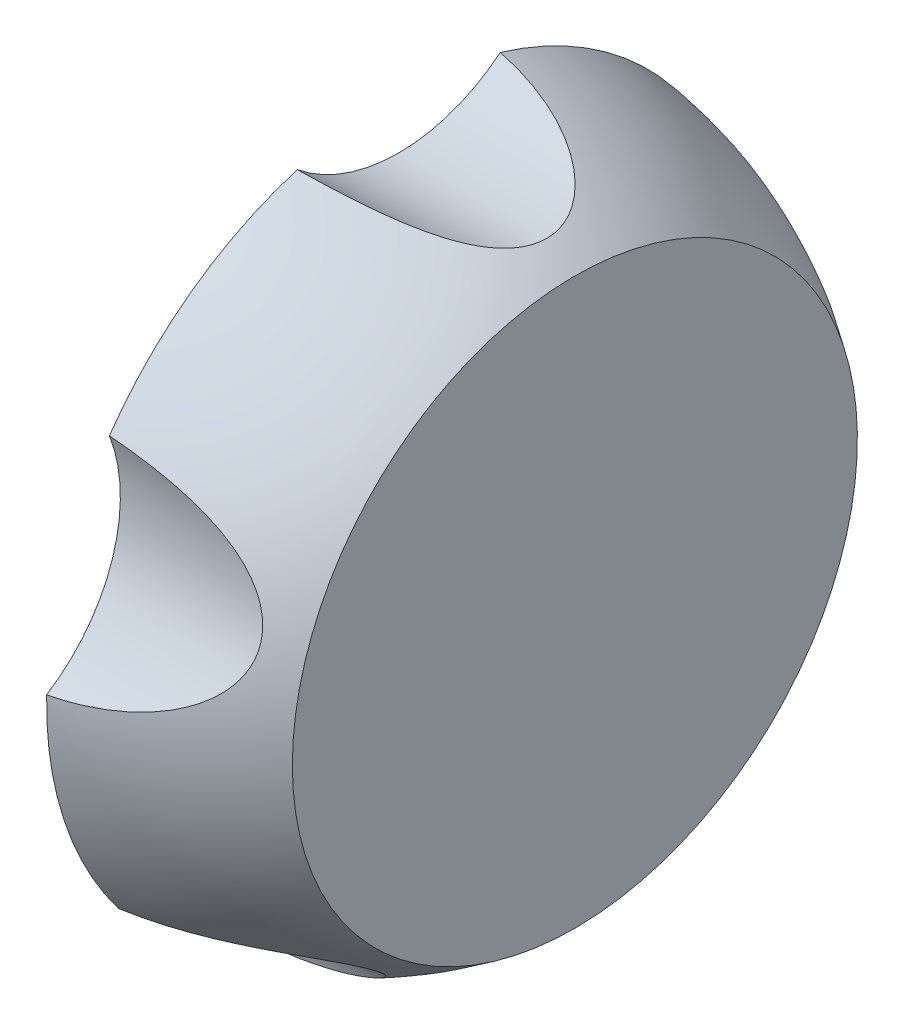
SolidWorks part; units mm, degrees
ref_plane "Front Plane" through (0, 0, 0) normal (0, 0, 1) x (1, 0, 0)
ref_plane "Top Plane" through (0, 0, 0) normal (0, 1, 0) x (1, 0, 0)
ref_plane "Right Plane" through (0, 0, 0) normal (1, 0, 0) x (0, 0, -1)
sketch "Sketch1" plane through (0, 0, 0) normal (0, 0, 1) x (1, 0, 0)
  line L2 (0, 38.1) -> (50.8, 38.1)
  line L3 (50.8, 38.1) -> (50.8, 0)
  line L4 (50.8, 0) -> (69.85, 0)
  line L5 (69.85, 0) -> (69.85, 112.0668)
  line L6 (0, 38.1) -> (0, 139.7)
  arc A0 (0, 139.7) -> (69.85, 112.0668) centre (-19.4087, -11.4591) cw
  dimension "D5" = 152.4
  dimension "D1" = 38.1
  dimension "D2" = 50.8
  dimension "D3" = 19.05
  dimension "D4" = 101.6
  dimension "D6" = 19.4087
revolve "Revolve1" add sketch "Sketch1" angle 360 about L4
sketch "Sketch2" plane through (69.85, 0, 0) normal (1, 0, 0) x (0, 0, -1)
  circle A2 centre (0, 182.8904) radius 63.5
  circle A3 centre (173.9391, 56.5162) radius 63.5
  circle A4 centre (107.5003, -147.9614) radius 63.5
  circle A5 centre (-107.5003, -147.9614) radius 63.5
  circle A6 centre (-173.9391, 56.5162) radius 63.5
  point P15 (0, 0)
  dimension "D1" = 127
  dimension "D2" = 5
extrude "Cut-Extrude2" cut sketch "Sketch2" against normal up to surface (69.85 mm away) up to face at (0, 0, 38.1)
